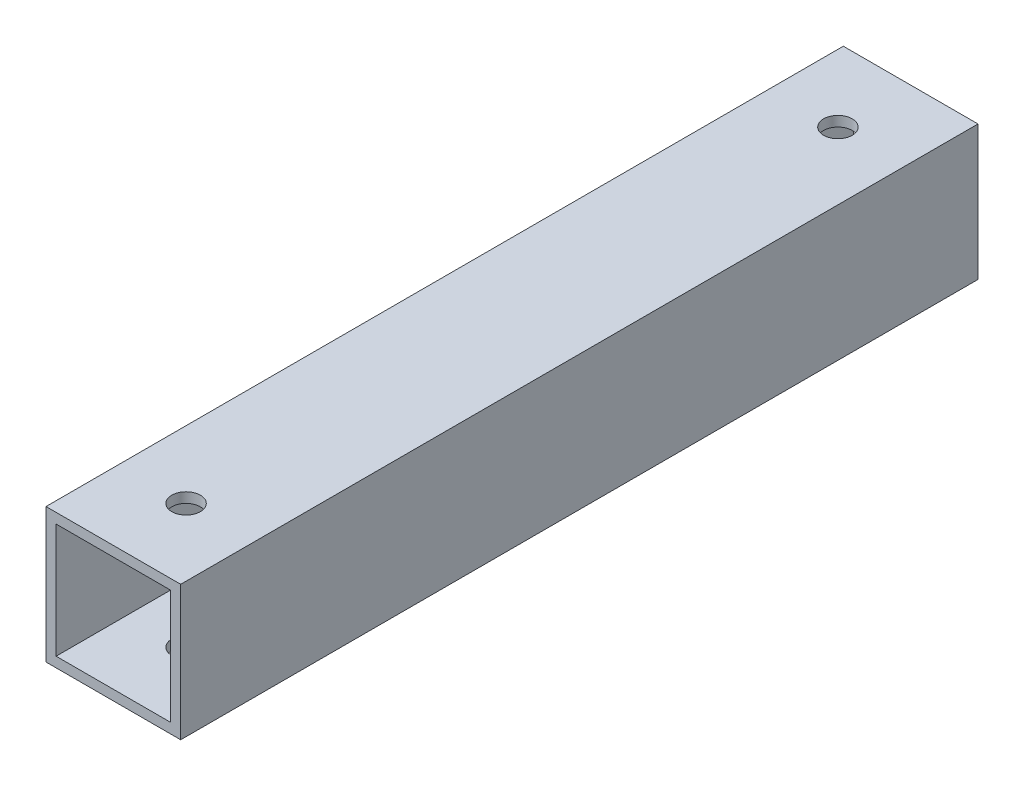
SolidWorks part; units mm, degrees
ref_plane "Front Plane" through (0, 0, 0) normal (0, 0, 1) x (1, 0, 0)
ref_plane "Top Plane" through (0, 0, 0) normal (0, 1, 0) x (1, 0, 0)
ref_plane "Right Plane" through (0, 0, 0) normal (1, 0, 0) x (0, 0, -1)
sketch "Sketch1" plane through (0, 0, 0) normal (0, 0, 1) x (1, 0, 0)
  line L0 (-8.5, -8.5) -> (8.5, -8.5)
  line L1 (-10, -10) -> (10, -10)
  line L2 (-10, -10) -> (-10, 10)
  line L3 (-10, 10) -> (10, 10)
  line L4 (10, -10) -> (10, 10)
  line L5 (-10, -10) -> (10, 10) construction
  line L6 (-10, 10) -> (10, -10) construction
  line L7 (8.5, -8.5) -> (8.5, 8.5)
  line L8 (-8.5, 8.5) -> (8.5, 8.5)
  line L9 (-8.5, -8.5) -> (-8.5, 8.5)
  point P0 (0, 0)
  dimension "D1" = 20
  dimension "D3" = 20
  dimension "D2" = 1.5
extrude "Boss-Extrude1" add sketch "Sketch1" against normal blind 118.4
sketch "Sketch2" plane through (0, 10, 0) normal (0, 1, 0) x (1, 0, 0)
  line L0 (10, 0) -> (-10, 0) construction
  line L1 (-10, 59.2) -> (10, 59.2) construction
  line L2 (-10, 118.4) -> (-10, 0) construction
  line L3 (10, 118.4) -> (10, 0) construction
  circle A0 centre (0, 10.8) radius 2.125
  circle A1 centre (0, 107.6) radius 2.125
  dimension "D1" = 4.25
  dimension "D2" = 10.8
extrude "Cut-Extrude1" cut sketch "Sketch2" against normal through all
